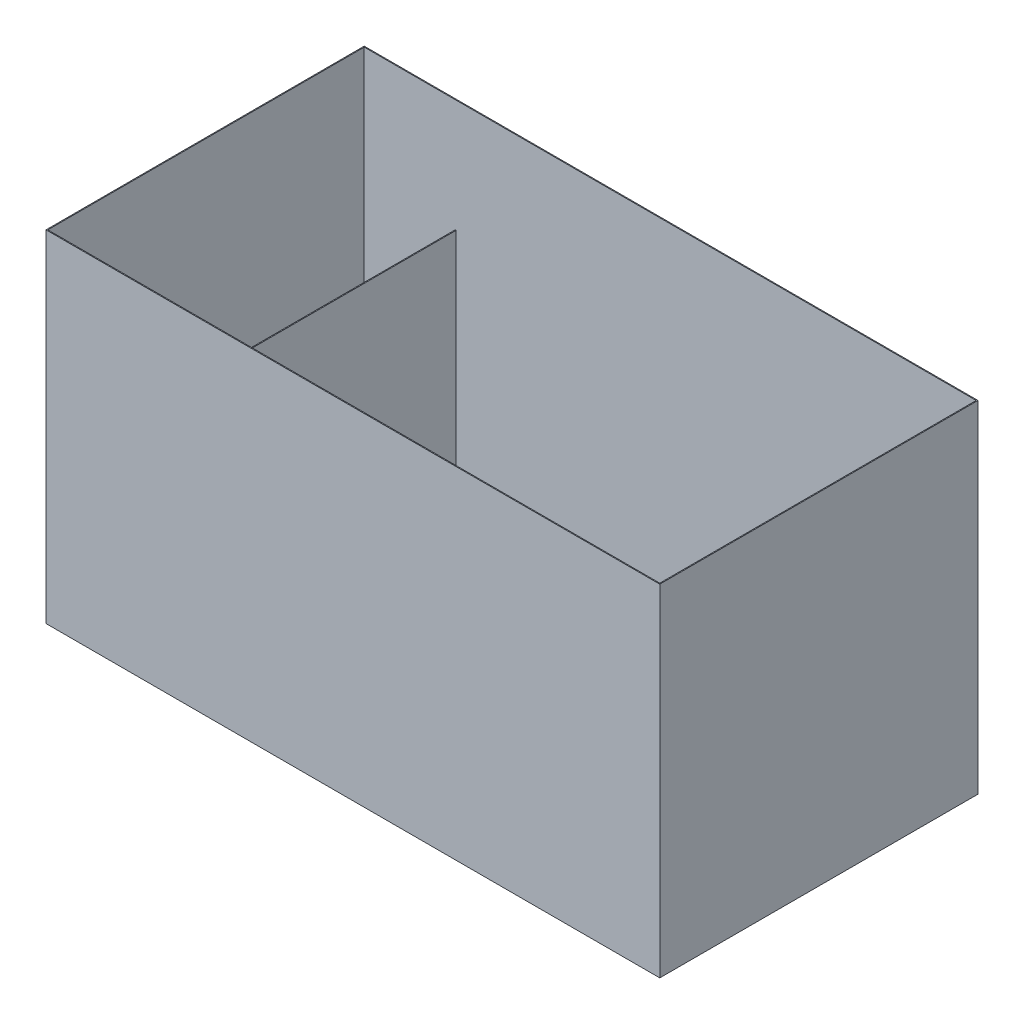
SolidWorks part; units mm, degrees
ref_plane "Спереди" through (0, 0, 0) normal (0, 0, 1) x (1, 0, 0)
ref_plane "Сверху" through (0, 0, 0) normal (0, 1, 0) x (1, 0, 0)
ref_plane "Справа" through (0, 0, 0) normal (1, 0, 0) x (0, 0, -1)
sketch "MASTER_FOOTPRINT" plane through (0, 0, 0) normal (0, 1, 0) x (1, 0, 0)
  line L1 (0, 0) -> (1350, 0)
  line L2 (0, 0) -> (0, 700)
  line L3 (0, 700) -> (1350, 700)
  line L4 (1350, 0) -> (1350, 700)
  dimension "D1" = 1350
  dimension "D2" = 700
extrude "BATH_BASE_PLATE" add sketch "MASTER_FOOTPRINT" along normal blind 750
shell "BATH_SHELL_2MM" thickness 2
sketch "Эскиз1" plane through (0, 0, 0) normal (1, 0, 0) x (0, 0, -1)
  line L1 (50, 100) -> (650, 100)
  line L2 (50, 100) -> (50, 550)
  line L3 (50, 550) -> (650, 550)
  line L4 (650, 100) -> (650, 550)
extrude "ORIENTATION_TEST" add sketch "Эскиз1" along normal blind 2 from offset 250 separate body
equation "\"AI_Q_Peak\"= 0.006"
equation "\"AI_B_Bath\"= 700"
equation "\"AI_L_Settle\"= 900"
equation "\"AI_L_Inlet\"= 250"
equation "\"AI_L_Outlet\"= 200"
equation "\"AI_L_Bath\"= 1350"
equation "\"AI_H_Water\"= 550"
equation "\"AI_H_Freeboard\"= 200"
equation "\"AI_H_Bath\"= 750"
equation "\"AI_Shell_Thickness\"= 2"
equation "\"AI_Inlet_DN\"= 100"
equation "\"AI_Weir_Width\"= 600"
equation "\"AI_Inlet_Baffle_Offset\"= 125"
equation "\"AI_Distributor_Open_Area\"= 0.28"
equation "\"AI_Distributor_Hole_Dia\"= 22"
equation "\"AI_Distributor_Blind_Zone\"= 110"
equation "\"AI_Outlet_Baffle_Depth\"= 250"
equation "\"AI_Screw_Diameter\"= 100"
equation "\"AI_Screw_Pitch\"= 100"
equation "\"AI_Screw_Angle\"= 30"
equation "\"AI_Screw_Rpm\"= 15"
equation "\"AI_Screw_Clearance\"= 5"
equation "\"AI_Liner_Thickness\"= 5"
equation "\"AI_Discharge_Height\"= 650"
equation "\"AI_Frame_Height\"= 500"
equation "\"D1@MASTER_FOOTPRINT\" = \"AI_L_Bath\""
equation "\"D2@MASTER_FOOTPRINT\" = \"AI_B_Bath\""
equation "\"D1@BATH_BASE_PLATE\" = \"AI_H_Bath\""
